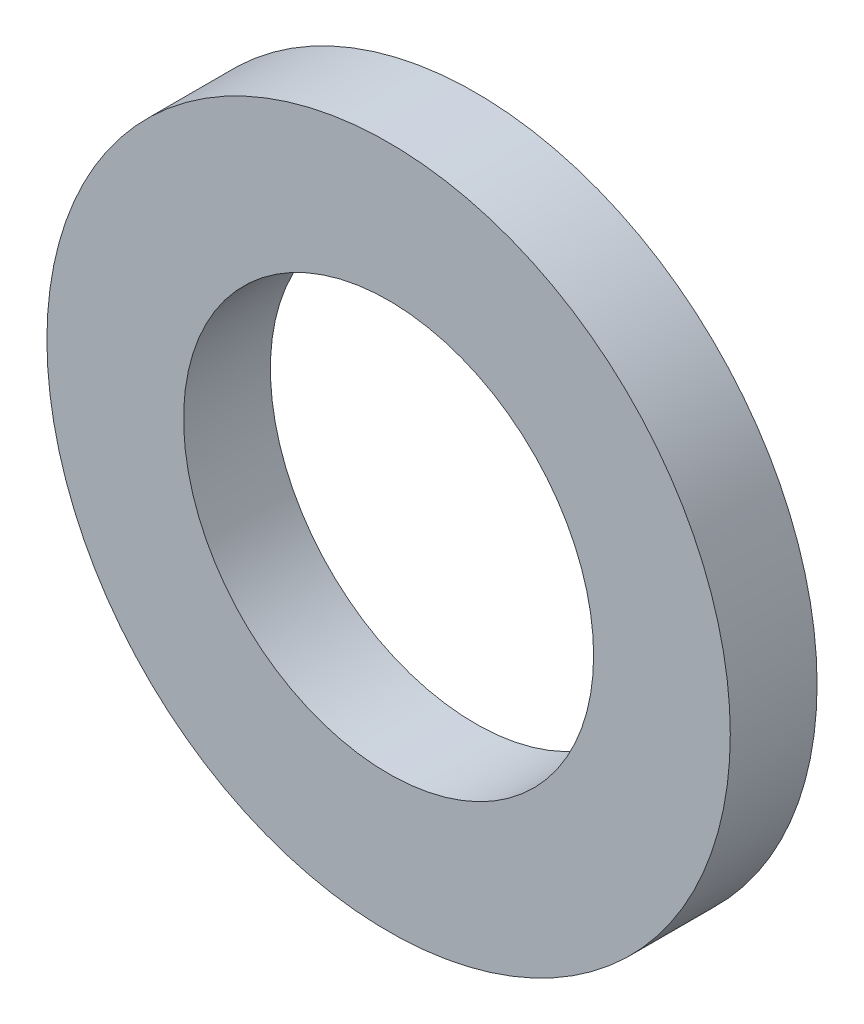
SolidWorks part; units mm, degrees
ref_plane "Front Plane" through (0, 0, 0) normal (0, 0, 1) x (1, 0, 0)
ref_plane "Top Plane" through (0, 0, 0) normal (0, 1, 0) x (1, 0, 0)
ref_plane "Right Plane" through (0, 0, 0) normal (1, 0, 0) x (0, 0, -1)
sketch "Sketch1" plane through (0, 0, 0) normal (0, 0, 1) x (1, 0, 0)
  circle A0 centre (0, 0) radius 12.5
  circle A1 centre (0, 0) radius 7.5
  dimension "D1" = 25
  dimension "D2" = 15
extrude "Boss-Extrude1" add sketch "Sketch1" along normal blind 3.175
